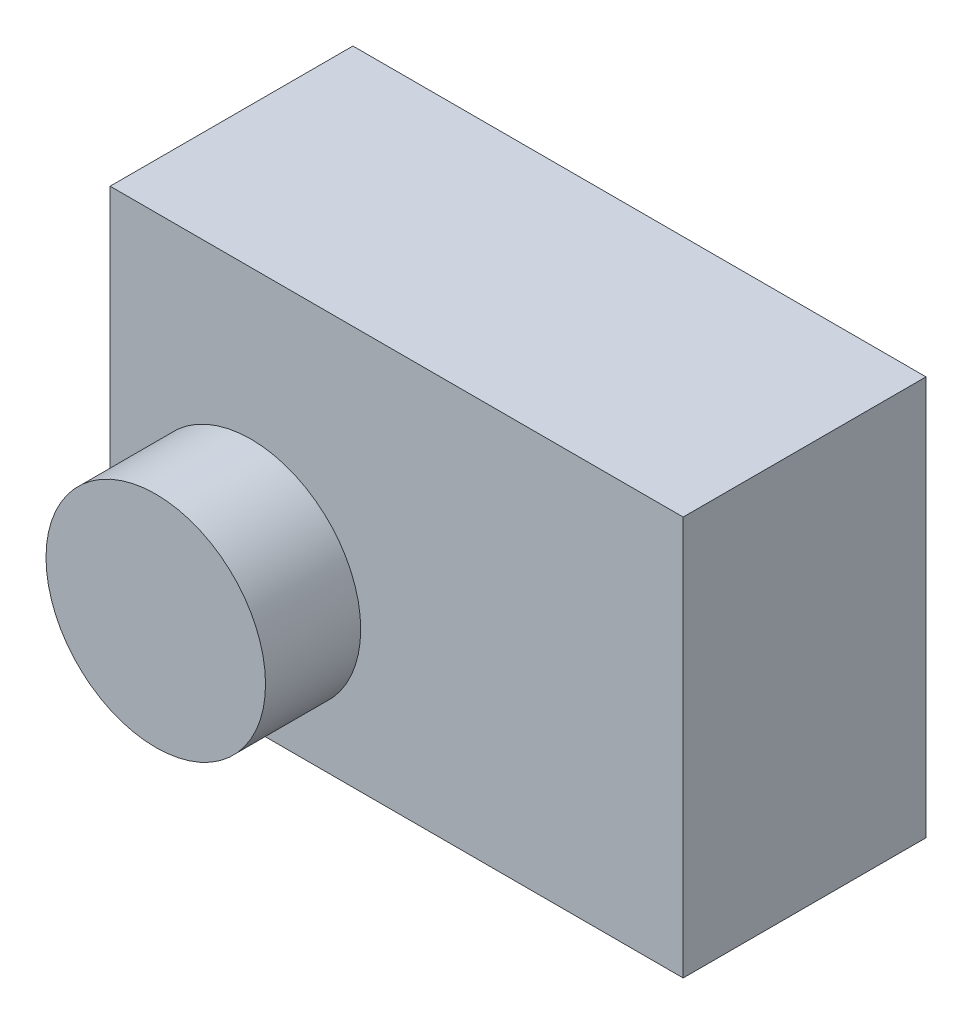
SolidWorks part; units mm, degrees
ref_plane "Plano frontal" through (0, 0, 0) normal (0, 0, 1) x (1, 0, 0)
ref_plane "Plano superior" through (0, 0, 0) normal (0, 1, 0) x (1, 0, 0)
ref_plane "Plano direito" through (0, 0, 0) normal (1, 0, 0) x (0, 0, -1)
sketch "Esboço1" plane through (0, 0, 0) normal (0, 0, 1) x (1, 0, 0)
  line L1 (29.5, -20.55) -> (-29.5, -20.55)
  line L2 (29.5, -20.55) -> (29.5, 20.55)
  line L3 (29.5, 20.55) -> (-29.5, 20.55)
  line L4 (-29.5, -20.55) -> (-29.5, 20.55)
  line L5 (29.5, -20.55) -> (-29.5, 20.55) construction
  line L6 (29.5, 20.55) -> (-29.5, -20.55) construction
  point P0 (0, 0)
  dimension "D1" = 59
  dimension "D2" = 41.1
extrude "Ressalto-extrusão1" add sketch "Esboço1" along normal blind 25
sketch "Esboço2" plane through (0, 0, 25) normal (0, 0, 1) x (1, 0, 0)
  line L2 (-29.5, 20.55) -> (-29.5, -20.55) construction
  line L3 (-29.5, -20.55) -> (29.5, -20.55) construction
  circle A0 centre (-15, -6.05) radius 11.3
  dimension "D1" = 22.6
  dimension "D2" = 3.2
  dimension "D3" = 3.2
extrude "Ressalto-extrusão2" add sketch "Esboço2" along normal blind 9.8
